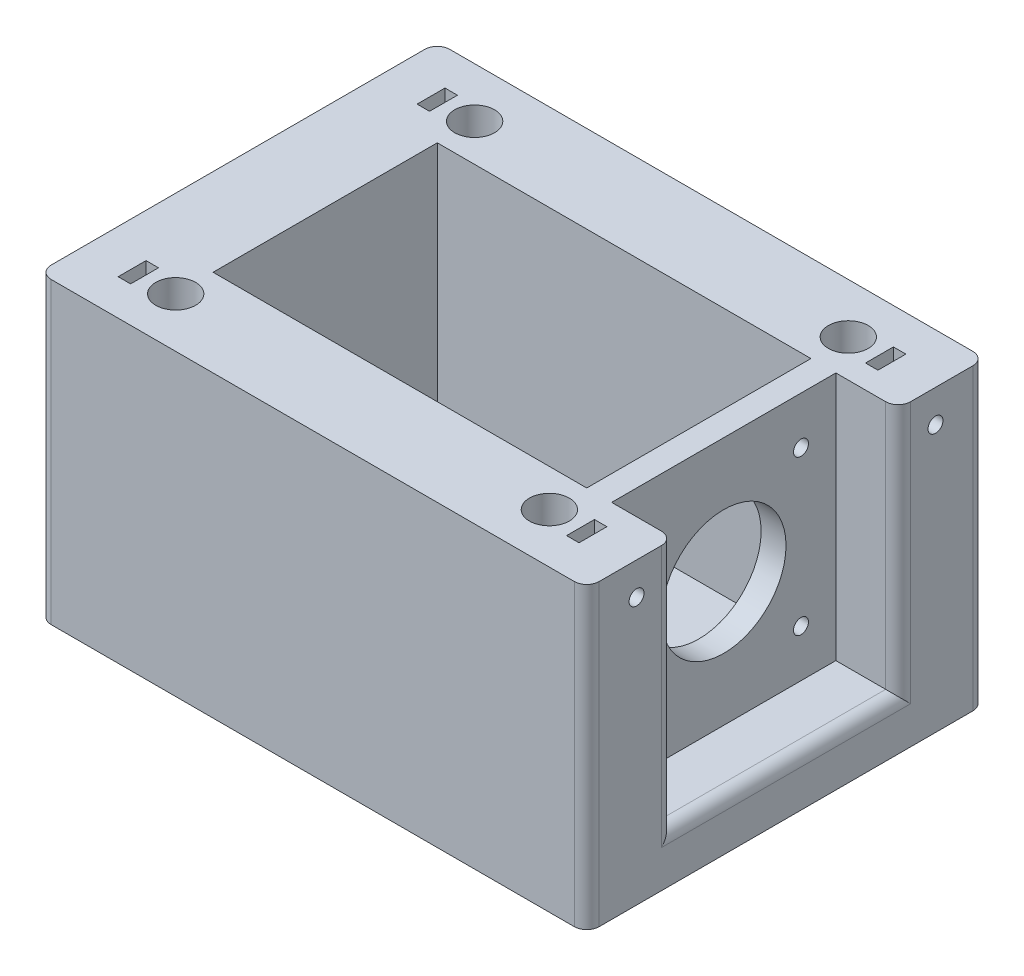
SolidWorks part; units mm, degrees
ref_plane "Front Plane" through (0, 0, 0) normal (0, 0, 1) x (1, 0, 0)
ref_plane "Top Plane" through (0, 0, 0) normal (0, 1, 0) x (1, 0, 0)
ref_plane "Right Plane" through (0, 0, 0) normal (1, 0, 0) x (0, 0, -1)
sketch "Sketch1" plane through (0, 0, 0) normal (0, 1, 0) x (1, 0, 0)
  line L1 (-55, 40) -> (55, 40)
  line L2 (-55, 40) -> (-55, -40)
  line L3 (-55, -40) -> (55, -40)
  line L4 (55, 40) -> (55, -40)
  line L5 (-55, 40) -> (55, -40) construction
  line L6 (-55, -40) -> (55, 40) construction
  point P0 (0, 0)
  dimension "D1" = 80
  dimension "D2" = 110
extrude "Boss-Extrude1" add sketch "Sketch1" along normal blind 60
sketch "Sketch2" plane through (0, 60, 0) normal (0, 1, 0) x (1, 0, 0)
  line L1 (-37.5, 22.5) -> (37.5, 22.5)
  line L2 (-37.5, 22.5) -> (-37.5, -22.5)
  line L3 (-37.5, -22.5) -> (37.5, -22.5)
  line L4 (37.5, 22.5) -> (37.5, -22.5)
  line L5 (-37.5, 22.5) -> (37.5, -22.5) construction
  line L6 (-37.5, -22.5) -> (37.5, 22.5) construction
  line L7 (-37.5, 30) -> (37.5, 30)
  line L8 (-37.5, 30) -> (-37.5, -30)
  line L9 (-37.5, -30) -> (37.5, -30)
  line L10 (37.5, 30) -> (37.5, -30)
  line L11 (-37.5, 30) -> (37.5, -30) construction
  line L12 (-37.5, -30) -> (37.5, 30) construction
  line L17 (55, -40) -> (55, 40) construction
  line L18 (42.5, 22.5) -> (55, 22.5)
  line L19 (42.5, 22.5) -> (42.5, -22.5)
  line L20 (42.5, -22.5) -> (55, -22.5)
  line L21 (55, 22.5) -> (55, -22.5)
  circle A0 centre (-37.5, 30) radius 4
  circle A1 centre (37.5, 30) radius 4
  circle A2 centre (37.5, -30) radius 4
  circle A3 centre (-37.5, -30) radius 4
  point P0 (0, 0)
  point P5 (0, 0)
  line M4 (55, -40) -> (55, 40)
  dimension "D5" = 8
  dimension "D1" = 45
  dimension "D2" = 75
  dimension "D3" = 60
  dimension "D4" = 75
  dimension "D8" = 5
  dimension "D9" = 45
  dimension "D10" = 0
  dimension "D11" = 0
  dimension "D6" = 2
  dimension "D7" = 2
extrude "Cut-Extrude2" cut sketch "Sketch2" against normal blind 50 contours L4 L1 L2 L3 | L7 A0 L8 | L8 A0 L7 | L10 A1 L7 | L7 A1 L10 | L8 A3 L9 | L9 A3 L8 | L9 A2 L10 | L10 A2 L9 | L19 L20 L18 M4
sketch "Sketch4" plane through (0, 60, 0) normal (0, 1, 0) x (1, 0, 0)
  line L1 (-45, 30) -> (45, 30)
  line L2 (-45, 30) -> (-45, -30)
  line L3 (-45, -30) -> (45, -30)
  line L4 (45, 30) -> (45, -30)
  line L5 (-45, 30) -> (45, -30) construction
  line L6 (-45, -30) -> (45, 30) construction
  line L7 (-46.25, 32.8) -> (-43.75, 32.8)
  line L8 (-46.25, 32.8) -> (-46.25, 27.2)
  line L9 (-46.25, 27.2) -> (-43.75, 27.2)
  line L10 (-43.75, 32.8) -> (-43.75, 27.2)
  line L11 (-46.25, 32.8) -> (-43.75, 27.2) construction
  line L12 (-46.25, 27.2) -> (-43.75, 32.8) construction
  line L20 (-46.25, -27.2) -> (-46.25, -32.8)
  line L21 (-46.25, -27.2) -> (-43.75, -27.2)
  line L22 (-43.75, -27.2) -> (-43.75, -32.8)
  line L23 (-46.25, -32.8) -> (-43.75, -32.8)
  line L24 (54.75, 32.8) -> (54.75, 27.2) [skipped]
  line L25 (54.75, 32.8) -> (57.25, 32.8) [skipped]
  line L26 (57.25, 32.8) -> (57.25, 27.2) [skipped]
  line L27 (54.75, 27.2) -> (57.25, 27.2) [skipped]
  line L28 (54.75, -27.2) -> (54.75, -32.8) [skipped]
  line L29 (54.75, -27.2) -> (57.25, -27.2) [skipped]
  line L30 (57.25, -27.2) -> (57.25, -32.8) [skipped]
  line L31 (54.75, -32.8) -> (57.25, -32.8) [skipped]
  line L32 (43.75, 32.8) -> (46.25, 32.8)
  line L33 (43.75, 32.8) -> (43.75, 27.2)
  line L34 (46.25, 32.8) -> (46.25, 27.2)
  line L35 (43.75, 27.2) -> (46.25, 27.2)
  line L36 (43.75, -27.2) -> (46.25, -27.2)
  line L37 (43.75, -27.2) -> (43.75, -32.8)
  line L38 (46.25, -27.2) -> (46.25, -32.8)
  line L39 (43.75, -32.8) -> (46.25, -32.8)
  point P0 (0, 0)
  point P5 (-45, 30)
  dimension "D1" = 2
  dimension "D2" = 5.6
  dimension "105" = 90
  dimension "D3" = 2.5
  dimension "D4" = 2
  dimension "D5" = 2
extrude "Cut-Extrude3" cut sketch "Sketch4" against normal blind 10 contours L10 L7 L8 L9 L2 L1 | L10 L1 L2 L9 | L20 L23 L22 L3 L2 L21 | L22 L21 L2 L3 | L36 L37 L3 L4 | L37 L39 L38 L36 L4 L3 | L4 L35 L34 L32 L33 L1 | L33 L35 L4 L1
sketch "Sketch5" plane through (55, 0, 0) normal (1, 0, 0) x (0, 0, -1)
  line L0 (-40, 60) -> (-22.5, 60) construction
  circle A0 centre (-30, 53.5) radius 1.5
  circle A1 centre (30, 53.5) radius 1.5
  dimension "D1" = 3
  dimension "D2" = 3
  dimension "D3" = 60
  dimension "D4" = 6.5
  dimension "D5" = 30
extrude "Cut-Extrude4" cut sketch "Sketch5" against normal blind 117
sketch "Sketch6" plane through (42.5, 0, 0) normal (1, 0, 0) x (0, 0, -1)
  line L1 (-15.5, 50.5) -> (15.5, 50.5)
  line L2 (-15.5, 50.5) -> (-15.5, 19.5)
  line L3 (-15.5, 19.5) -> (15.5, 19.5)
  line L4 (15.5, 50.5) -> (15.5, 19.5)
  line L5 (-15.5, 50.5) -> (15.5, 19.5) construction
  line L6 (-15.5, 19.5) -> (15.5, 50.5) construction
  line L7 (-22.5, 10) -> (22.5, 10) construction
  circle A0 centre (0, 35) radius 12.5
  circle A1 centre (-15.5, 50.5) radius 1.5
  circle A2 centre (15.5, 50.5) radius 1.5
  circle A3 centre (15.5, 19.5) radius 1.5
  circle A4 centre (-15.5, 19.5) radius 1.5
  point P0 (0, 35)
  point P15 (31, 35)
  point P18 (31, 4)
  point P21 (0, 4)
  dimension "D4" = 25
  dimension "D5" = 3
  dimension "D1" = 31
  dimension "D2" = 31
  dimension "D3" = 9.5
  dimension "D6" = 2
  dimension "D7" = 2
extrude "Cut-Extrude5" cut sketch "Sketch6" against normal blind 5 contours A0 | L1 A1 L2 | L2 A1 L1 | L1 A2 L4 | L4 A2 L1 | L3 A3 L4 | L4 A3 L3 | L3 A4 L2 | L2 A4 L3
fillet "Fillet1" radius 2.5 7 edges at (-55, 30, 40) (-55, 30, -40) (55, 30, -40) (55, 30, 40) (55, 35, -22.5) (55, 10, 0) (55, 35, 22.5)
